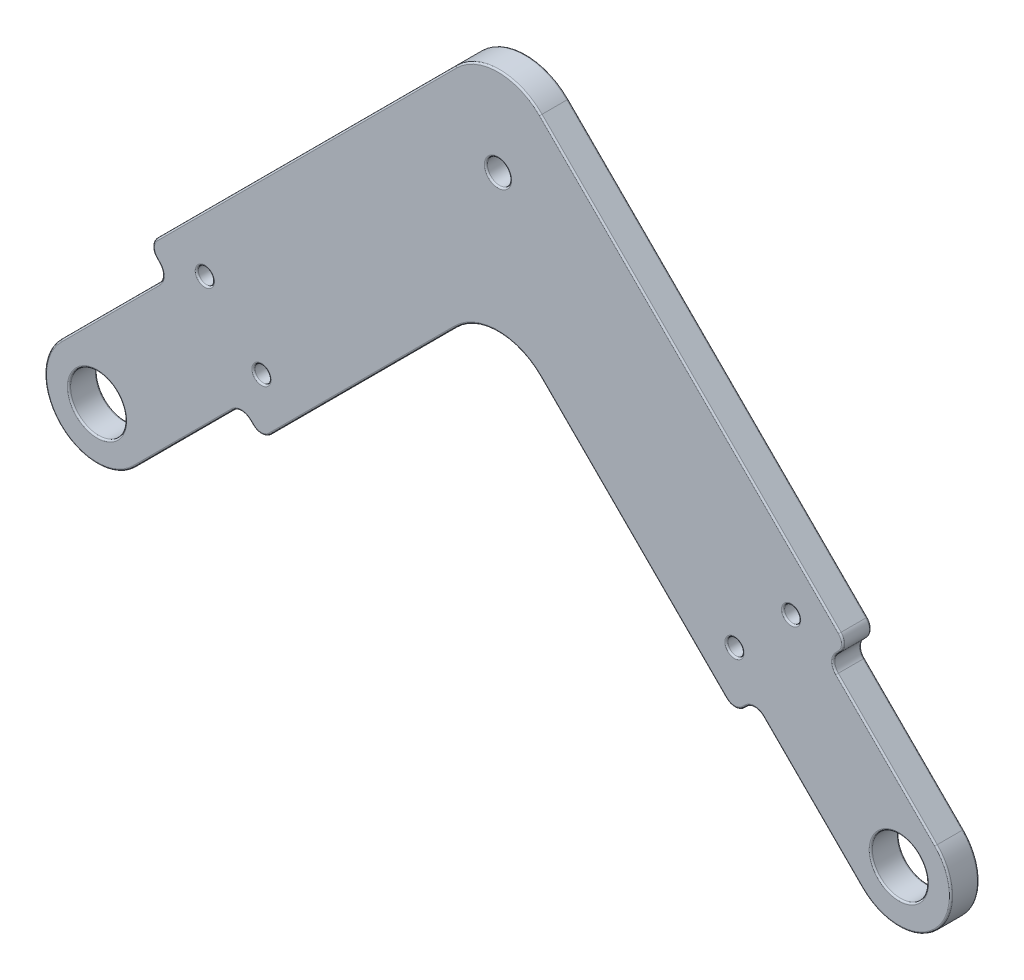
SolidWorks part; units mm, degrees
ref_plane "Front Plane" through (0, 0, 0) normal (0, 0, 1) x (1, 0, 0)
ref_plane "Top Plane" through (0, 0, 0) normal (0, 1, 0) x (1, 0, 0)
ref_plane "Right Plane" through (0, 0, 0) normal (1, 0, 0) x (0, 0, -1)
sketch "Sketch1" plane through (0, 0, 0) normal (0, 0, 1) x (1, 0, 0)
  line L0 (-100, 0) -> (100, 0) construction
  line L1 (-100, 0) -> (0, 100) construction
  line L2 (0, 100) -> (100, 0) construction
  line L3 (0, 0) -> (-50, 50) construction
  line L4 (-40, 60) -> (40, 60) construction
  line L5 (0, 100) -> (0, 60) construction
  circle A0 centre (-100, 0) radius 20
  circle A1 centre (0, 0) radius 20
  circle A2 centre (100, 0) radius 20
  point P2 (0, 0)
  dimension "D5" = 40
  dimension "D1" = 200
  dimension "D2" = 90
  dimension "D3" = 90
  dimension "D4" = 80
sketch "Sketch2" plane through (0, 0, 0) normal (0, 0, 1) x (1, 0, 0)
  line L0 (-56.5165, 43.4835) -> (-40, 60) construction
  line L1 (-100, 0) -> (0, 100) construction
  line L2 (-40, 60) -> (40, 60) construction
  line L3 (40, 60) -> (86.565, 13.435) construction
  line L4 (0, 100) -> (100, 0) construction
  line L5 (-49.4454, 36.4124) -> (-35.8579, 50)
  line L6 (-35.8579, 50) -> (35.8579, 50)
  line L7 (35.8579, 50) -> (79.4939, 6.364)
  line L8 (-63.5876, 50.5546) -> (-44.1421, 70)
  line L9 (-44.1421, 70) -> (44.1421, 70)
  line L10 (44.1421, 70) -> (93.636, 20.5061)
  line L11 (-63.5876, 50.5546) -> (-49.4454, 36.4124)
  line L12 (93.636, 20.5061) -> (79.4939, 6.364)
  line L13 (90.9809, 17.8509) -> (104.534, 4.6576)
  line L14 (82.1491, 9.0191) -> (95.3424, -4.534)
  line L15 (90.1005, 24.0416) -> (75.9584, 9.8995)
  line L16 (0, 100) -> (0, 60) construction
  line L17 (-6, 70) -> (-3.4532, 85.4203)
  line L18 (6, 70) -> (3.4532, 85.4203)
  circle A0 centre (100, 0) radius 3.5
  circle A1 centre (100, 0) radius 10 construction
  arc A2 (95.3424, -4.534) -> (104.534, 4.6576) centre (100, 0) ccw
  circle A3 centre (100, 0) radius 0.5
  circle A4 centre (100, 0) radius 20 construction
  circle A5 centre (100, 0) radius 6.5 construction
  circle A6 centre (79.4939, 13.435) radius 1
  circle A7 centre (86.565, 20.5061) radius 1
  circle A8 centre (0, 60) radius 1.5
  circle A9 centre (0, 84.85) radius 1.5
  arc A10 (3.4532, 85.4203) -> (-3.4532, 85.4203) centre (0, 84.85) ccw
  circle A11 centre (0, 84.85) radius 3.5 construction
  circle A12 centre (-50, 50) radius 1.5
  dimension "D4" = 20
  dimension "D5" = 7
  dimension "D10" = 2
  dimension "D13" = 3
  dimension "D18" = 3
  dimension "D3" = 27.5
  dimension "D8" = 19
  dimension "D9" = 5
  dimension "D11" = 5
  dimension "D12" = 5
  dimension "D14" = 14.85
  dimension "D16" = 6
  dimension "D17" = 6
  dimension "D1" = 10
  dimension "D2" = 10
  dimension "D6" = 3
  dimension "D7" = 3
  dimension "D15" = 2
sketch "Sketch3" plane through (0, 0, 0) normal (0, 0, 1) x (1, 0, 0)
  line L1 (-100, 0) -> (0, 100) construction
  line L2 (-86.565, 13.435) -> (-50, 50) construction
  line L3 (-50, 50) -> (-13.435, 13.435) construction
  line L4 (0, 0) -> (-50, 50) construction
  line L5 (-93.636, 20.5061) -> (-50, 64.1421)
  line L6 (-50, 64.1421) -> (-6.364, 20.5061)
  line L7 (-79.4939, 6.364) -> (-50, 35.8579)
  line L8 (-50, 35.8579) -> (-20.5061, 6.364)
  line L9 (-93.636, 20.5061) -> (-50, 64.1421) construction
  line L10 (-79.4939, 6.364) -> (-50, 35.8579) construction
  line L11 (-93.636, 20.5061) -> (-79.4939, 6.364)
  line L12 (-6.364, 20.5061) -> (-20.5061, 6.364)
  line L13 (-104.5962, 4.5962) -> (-91.2218, 17.9706)
  line L14 (-95.4038, -4.5962) -> (-82.0294, 8.7782)
  line L15 (-17.9706, 8.7782) -> (-4.5962, -4.5962)
  line L16 (-8.7782, 17.9706) -> (4.5962, 4.5962)
  line L17 (-90.1005, 24.0416) -> (-75.9584, 9.8995) construction
  line L18 (-24.0416, 9.8995) -> (-9.8995, 24.0416) construction
  circle A0 centre (-100, 0) radius 10 construction
  circle A1 centre (-100, 0) radius 3.5
  circle A2 centre (0, 0) radius 3.5
  circle A3 centre (0, 0) radius 10 construction
  arc A4 (-4.5962, -4.5962) -> (4.5962, 4.5962) centre (0, 0) ccw
  arc A5 (-104.5962, 4.5962) -> (-95.4038, -4.5962) centre (-100, 0) ccw
  circle A6 centre (-86.565, 20.5061) radius 1
  circle A7 centre (-100, 0) radius 20 construction
  circle A8 centre (0, 0) radius 20 construction
  circle A9 centre (-100, 0) radius 6.5 construction
  circle A10 centre (0, 0) radius 6.5 construction
  circle A11 centre (-79.4939, 13.435) radius 1
  circle A12 centre (-20.5061, 13.435) radius 1
  circle A13 centre (-13.435, 20.5061) radius 1
  circle A14 centre (-50, 50) radius 1.5 construction
  circle A15 centre (-50, 50) radius 1.5
  dimension "D1" = 20
  dimension "D2" = 7
  dimension "D8" = 2
  dimension "D6" = 19
  dimension "D7" = 19
  dimension "D9" = 5
  dimension "D10" = 5
  dimension "D11" = 5
  dimension "D12" = 5
  dimension "D13" = 5
  dimension "D14" = 5
  dimension "D3" = 3
  dimension "D4" = 10
  dimension "D5" = 10
sketch "Sketch4" plane through (0, 0, 0) normal (0, 0, 1) x (1, 0, 0)
  line L0 (-57.5, 94.8011) -> (57.5, 94.8011)
  line L1 (57.5, 94.8011) -> (57.5, 84.8011)
  line L2 (57.5, 84.8011) -> (44.1421, 70)
  line L3 (44.1421, 70) -> (-44.1421, 70)
  line L4 (-44.1421, 70) -> (-57.5, 84.8011)
  line L5 (-57.5, 84.8011) -> (-57.5, 94.8011)
  line L6 (4, 60) -> (4, 70)
  line L7 (-4, 60) -> (-4, 70)
  line L9 (-22.5, 86.3011) -> (22.5, 86.3011) construction
  line L10 (-22.5, 90.8011) -> (22.5, 90.8011)
  line L11 (-22.5, 81.8011) -> (22.5, 81.8011)
  circle A0 centre (0, 60) radius 1.5 construction
  circle A1 centre (0, 60) radius 1.5
  arc A2 (-4, 60) -> (4, 60) centre (0, 60) ccw
  circle A3 centre (0, 60) radius 4 construction
  arc A4 (-22.5, 90.8011) -> (-22.5, 81.8011) centre (-22.5, 86.3011) ccw
  arc A5 (22.5, 81.8011) -> (22.5, 90.8011) centre (22.5, 86.3011) ccw
  point P19 (0, 86.3011)
  dimension "D1" = 115
  dimension "D2" = 10
  dimension "D3" = 2.5
  dimension "D4" = 45
  dimension "D5" = 9
  dimension "D6" = 4
sketch "Sketch5" plane through (0, 0, 0) normal (0, 0, 1) x (1, 0, 0)
  line L0 (-95.4038, -4.5962) -> (-82.0294, 8.7782) construction
  line L1 (-104.5962, 4.5962) -> (-91.2218, 17.9706) construction
  line L2 (-17.9706, 8.7782) -> (-4.5962, -4.5962) construction
  line L3 (-8.7782, 17.9706) -> (4.5962, 4.5962) construction
  line L4 (-95.4038, -4.5962) -> (-82.0294, 8.7782)
  line L5 (-104.5962, 4.5962) -> (-91.2218, 17.9706)
  line L6 (-50, 64.1421) -> (-93.636, 20.5061)
  line L7 (-6.364, 20.5061) -> (-50, 64.1421)
  line L8 (-20.5061, 6.364) -> (-6.364, 20.5061)
  line L9 (-50, 35.8579) -> (-20.5061, 6.364)
  line L10 (-79.4939, 6.364) -> (-50, 35.8579)
  line L11 (-93.636, 20.5061) -> (-79.4939, 6.364)
  line L12 (-50, 64.1421) -> (-93.636, 20.5061)
  line L13 (-6.364, 20.5061) -> (-50, 64.1421)
  line L15 (-50, 35.8579) -> (-20.5061, 6.364)
  line L16 (-79.4939, 6.364) -> (-50, 35.8579)
  line L18 (-17.9706, 8.7782) -> (-4.5962, -4.5962)
  line L19 (-8.7782, 17.9706) -> (4.5962, 4.5962)
  line L20 (-93.636, 20.5061) -> (-91.2218, 17.9706)
  line L21 (-79.4939, 6.364) -> (-82.0294, 8.7782)
  line L22 (-20.5061, 6.364) -> (-17.9706, 8.7782)
  line L23 (-6.364, 20.5061) -> (-8.7782, 17.9706)
  arc A0 (-104.5962, 4.5962) -> (-95.4038, -4.5962) centre (-100, 0) ccw construction
  circle A1 centre (0, 0) radius 3.5
  circle A2 centre (0, 0) radius 3.5
  circle A3 centre (-100, 0) radius 3.5
  circle A4 centre (-100, 0) radius 3.5
  circle A5 centre (-86.565, 20.5061) radius 1
  circle A6 centre (-86.565, 20.5061) radius 1
  circle A7 centre (-50, 50) radius 1.5
  circle A8 centre (-50, 50) radius 1.5
  circle A9 centre (-13.435, 20.5061) radius 1
  circle A10 centre (-13.435, 20.5061) radius 1
  circle A11 centre (-20.5061, 13.435) radius 1
  circle A12 centre (-20.5061, 13.435) radius 1
  circle A13 centre (-79.4939, 13.435) radius 1
  circle A14 centre (-79.4939, 13.435) radius 1
  arc A15 (-4.5962, -4.5962) -> (4.5962, 4.5962) centre (0, 0) ccw construction
  arc A16 (-104.5962, 4.5962) -> (-95.4038, -4.5962) centre (-100, 0) ccw
  arc A17 (-4.5962, -4.5962) -> (4.5962, 4.5962) centre (0, 0) ccw
  dimension "D1" = 0
  dimension "D2" = 0
  dimension "D3" = 0
  dimension "D4" = 0
  dimension "D5" = 0
  dimension "D6" = 0
  dimension "D7" = 0
  dimension "D8" = 0
extrude "Boss-Extrude1" add sketch "Sketch5" along normal blind 3.5
fillet "Fillet1" radius 7.5 2 edges at (-50, 35.8579, 1.75) (-50, 64.1421, 1.75)
fillet "Fillet2" radius 1.5 8 edges at (-91.2218, 17.9706, 1.75) (-93.636, 20.5061, 1.75) (-82.0294, 8.7782, 1.75) (-79.4939, 6.364, 1.75) (-17.9706, 8.7782, 1.75) (-20.5061, 6.364, 1.75) (-8.7782, 17.9706, 1.75) (-6.364, 20.5061, 1.75)
fillet "Fillet3" radius 0.2 62 edges at (-78.4939, 13.435, 0) (-78.4939, 13.435, 3.5) (-19.5061, 13.435, 0) (-19.5061, 13.435, 3.5) (-12.435, 20.5061, 0) (-12.435, 20.5061, 3.5) (-48.5, 50, 0) (-48.5, 50, 3.5) (-85.565, 20.5061, 0) (-85.565, 20.5061, 3.5) (-96.5, 0, 0) (-96.5, 0, 3.5) (3.5, 0, 0) (3.5, 0, 3.5) (-92.4289, 19.2384, 0) (-98.4265, 10.7659, 0) (-104.5962, -4.5962, 0) (-89.2341, 1.5735, 0) (-80.7616, 7.5711, 0) (-66.8811, 18.9768, 0) (-33.1189, 18.9768, 0) (-19.2384, 7.5711, 0) (-10.7659, 1.5735, 0) (4.5962, -4.5962, 0) (-1.5735, 10.7659, 0) (-7.5711, 19.2384, 0) (-26.0478, 40.19, 0) (-73.9522, 40.19, 0) (-92.4289, 19.2384, 3.5) (-98.4265, 10.7659, 3.5) (-104.5962, -4.5962, 3.5) (-89.2341, 1.5735, 3.5) (-80.7616, 7.5711, 3.5) (-66.8811, 18.9768, 3.5) (-33.1189, 18.9768, 3.5) (-19.2384, 7.5711, 3.5) (-10.7659, 1.5735, 3.5) (4.5962, -4.5962, 3.5) (-1.5735, 10.7659, 3.5) (-7.5711, 19.2384, 3.5) (-73.9522, 40.19, 3.5) (-50, 61.0355, 0) (-50, 61.0355, 3.5) (-50, 32.7513, 0) (-50, 32.7513, 3.5) (-6.9597, 20.4988, 0) (-20.4988, 6.9597, 0) (-79.5012, 6.9597, 0) (-93.0403, 20.4988, 0) (-6.9597, 20.4988, 3.5) (-20.4988, 6.9597, 3.5) (-79.5012, 6.9597, 3.5) (-93.0403, 20.4988, 3.5) (-91.8176, 17.9779, 0) (-91.8176, 17.9779, 3.5) (-82.0221, 8.1824, 0) (-82.0221, 8.1824, 3.5) (-17.9779, 8.1824, 0) (-17.9779, 8.1824, 3.5) (-8.1824, 17.9779, 0) (-8.1824, 17.9779, 3.5) (-26.0478, 40.19, 3.5)
